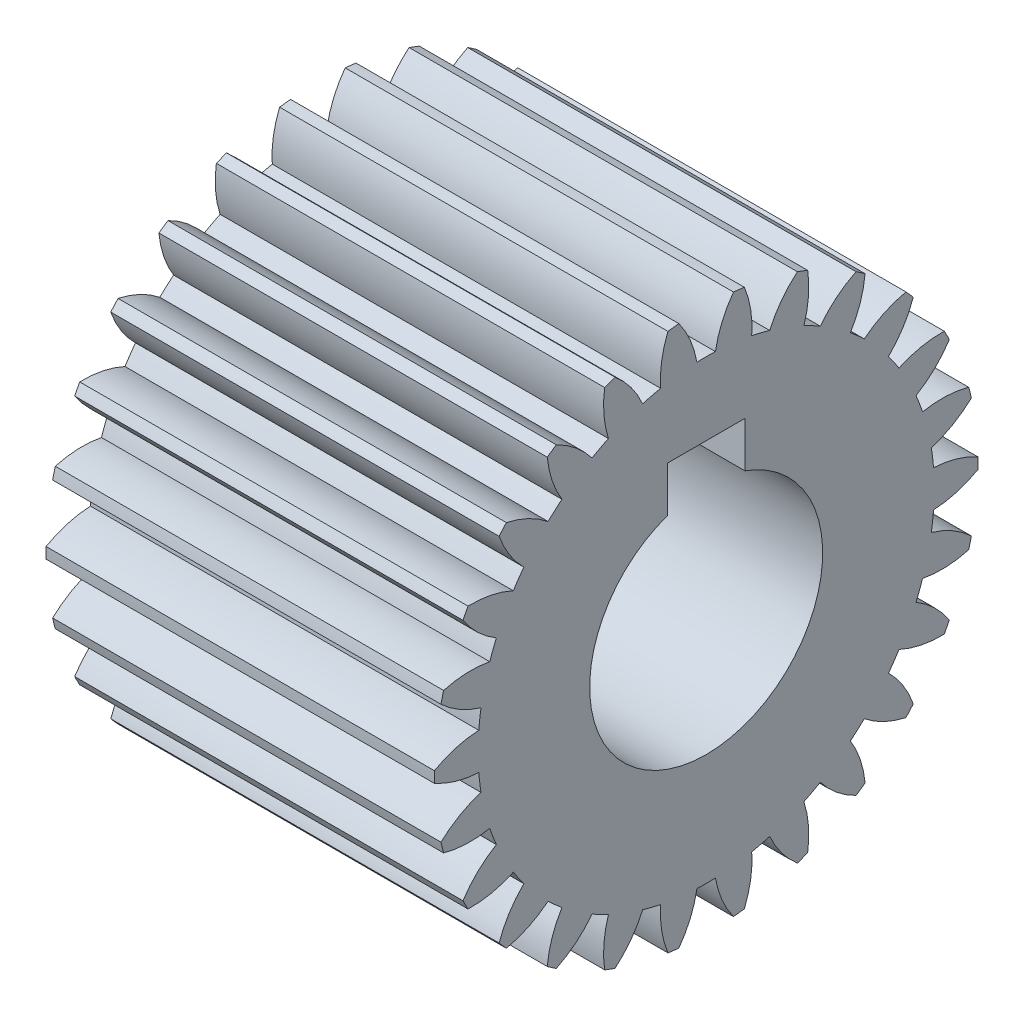
SolidWorks part; units mm, degrees
ref_plane "Plane1" through (0, 0, 0) normal (0, 0, 1) x (1, 0, 0)
ref_plane "Plane2" through (0, 0, 0) normal (0, 1, 0) x (1, 0, 0)
ref_plane "Plane3" through (0, 0, 0) normal (1, 0, 0) x (0, 0, -1)
sketch "HoldingSke" plane through (0, 0, 0) normal (0, 1, 0) x (1, 0, 0)
  line L0 (0, 0) -> (1.7976, -0.8767)
  line L1 (-15, 0) -> (100, 0) construction
  line L2 (0, 0) -> (-2.1039, 2.3779)
  line L3 (0, 0) -> (-11.863, 4.5341)
  line L4 (0, 0) -> (7.762, 3.7858)
  line L5 (0, 0) -> (-46.8476, -17.4728)
  line L6 (0, 0) -> (-8.2896, -5.593)
  line L7 (-2.1039, 2.3779) -> (8.6586, 51.2059)
  line L8 (-76.2, 54.61) -> (-75.2, 54.61)
  line L9 (-71.009, 38.7566) -> (-53.1078, 45.2721)
  line L10 (-76.2, 71.12) -> (104.1128, 71.12)
  line L11 (0, 0) -> (-10, 0)
  line L12 (-76.2, 101.6) -> (-76.181, 101.6)
  line L13 (24.9733, 27.94) -> (52.9518, 28.4284)
  line L14 (24.9733, 27.94) -> (24.9743, 27.94)
  line L15 (24.9733, 27.94) -> (100.4006, 29.5858)
  line L16 (-63.627, -0.5) -> (-12.827, -0.5)
  circle A0 centre (0, 0) radius 3
  circle A1 centre (0, 0) radius 5.874
  circle A2 centre (0, 0) radius 37.5
  circle A3 centre (0, 0) radius 3
  dimension "MHD" = 11.748
  dimension "Hub_dia" = 75
  dimension "Bore" = 6
  dimension "MBD" = 6
  dimension "Num_teeth" = 26
  dimension "Pitch" = 2
  dimension "Overall_len" = 50
  dimension "Show_teeth" = 26
  dimension "Thickness" = 10
  dimension "OAL" = 50.0001
  dimension "T_dim" = 1
  dimension "Ap" = 20
  dimension "H" = 19.05
  dimension "Pitch_radius" = 180.3128
  dimension "Width" = 10
  dimension "Backlash" = 0.019
  dimension "Addendum_fac" = 1
  dimension "Dedendum_fac" = 1.25
  dimension "Clearance_fac" = 0.25
  dimension "Dedendum_add" = 0.001
  dimension "Module" = 0.5
sketch "BasProSke" plane through (0, 0, 0) normal (0, 1, 0) x (1, 0, 0)
  line L0 (-10, 0) -> (60, 0) construction
  line L1 (0, 0) -> (0, 7)
  line L2 (0, 0) -> (10, 0)
  line L3 (10, 0) -> (10, 7)
  line L4 (10, 7) -> (0, 7)
  dimension "Thickness" = 10
  dimension "Diameter" = 14
revolve "Base-Revolve" add sketch "BasProSke" angle 360 about L0
sketch "TooCutSke" plane through (0, 0, 0) normal (1, 0, 0) x (0, 0, -1)
  line L1 (0, 0) -> (0, 107) construction
  line L2 (0, 0) -> (-0.4257, 6.486) construction
  line L3 (0, 0) -> (-1.5646, 12.8855) construction
  line L4 (-0.4257, 6.486) -> (-0.7823, 6.4427) construction
  arc A0 (0.2384, 5.8692) -> (-0.2384, 5.8692) centre (0, 0) ccw
  arc A1 (0.7209, 6.9883) -> (-0.7209, 6.9883) centre (0, 0) ccw
  circle A2 centre (0, 0) radius 6.5 construction
  circle A3 centre (0, 0) radius 6.108 construction
  arc A4 (-0.2384, 5.8692) -> (-0.7209, 6.9883) centre (-2.8007, 5.4281) ccw
  arc A5 (0.7209, 6.9883) -> (0.2384, 5.8692) centre (2.8007, 5.4281) ccw
  dimension "Root_dia" = 11.748
  dimension "Overcut_dia" = 14.0508
  dimension "Pitch_dia" = 13
  dimension "Base_dia" = 12.216
  dimension "Flank_rad" = 2.6
  dimension "Half_ang" = 6.923
  dimension "Half_CT" = 0.3592
extrude "ToothCut" cut sketch "TooCutSke" along normal through all
fillet "Breaks" [suppressed] radius 0.01
fillet "RootFillets" [suppressed] radius 0.126
pattern_circular "TeethCuts" count 26 every 13.846 about axis through (-10, 0, 0) along (1, 0, 0) of "ToothCut", "RootFillets", "Breaks"
sketch "HubNeaOneSke" plane through (0, 0, 0) normal (-1, 0, 0) x (0, 0, 1)
  circle A0 centre (0, 0) radius 5.874
  dimension "Diameter" = 11.748
extrude "HubNearOne" [suppressed] add sketch "HubNeaOneSke" along normal blind 40.0001
sketch "HubNeaBotSke" plane through (0, 0, 0) normal (-1, 0, 0) x (0, 0, 1)
  circle A0 centre (0, 0) radius 5.874
  dimension "Diameter" = 11.748
extrude "HubNearBoth" [suppressed] add sketch "HubNeaBotSke" along normal blind 20
ref_plane "FarPln" through (10, 0, 0) normal (1, 0, 0) x (0, 0, -1)
sketch "HubFarSke" plane through (10, 0, 0) normal (1, 0, 0) x (0, 0, -1)
  circle A0 centre (0, 0) radius 5.874
  dimension "Diameter" = 11.748
extrude "HubFar" [suppressed] add sketch "HubFarSke" along normal blind 20
sketch "BorSke" plane through (0, 0, 0) normal (1, 0, 0) x (0, 0, -1)
  circle A0 centre (0, 0) radius 3
  dimension "Diameter" = 6
extrude "Bore" cut sketch "BorSke" along normal mid plane 100.0001
sketch "KeySke" plane through (0, 0, 0) normal (1, 0, 0) x (0, 0, -1)
  line L0 (-1, 0) -> (-1, 4)
  line L1 (-1, 4) -> (1, 4)
  line L2 (1, 4) -> (1, 0)
  line L3 (0, 0) -> (0, 34) construction
  line L4 (-1, 0) -> (1, 0)
  dimension "Offset" = 4
  dimension "Width" = 2
extrude "Keyway" cut sketch "KeySke" along normal mid plane 100.0001
pattern_circular "Keyway2" [suppressed] count 2 every 90 about axis through (-10, 0, 0) along (1, 0, 0)
equation "' \"Module@HoldingSke\" = 6.35"
equation "' \"Num_teeth@HoldingSke\" = 12"
equation "' \"Ap@HoldingSke\" =  20"
equation "' \"Ap@HoldingSke\" = 20"
equation "' \"Width@HoldingSke\" = 0.5 * 25.4"
equation "' \"Hub_dia@HoldingSke\"= 1 * 25.4"
equation "' \"Hub_dia@HoldingSke\" = 1 * 25.4"
equation "' \"Overall_len@HoldingSke\" = 1.0 * 25.4"
equation "' \"Bore@HoldingSke\" = 0.75 * 25.4"
equation "' \"T_dim@HoldingSke\" = 0.1 * 25.4"
equation "' \"Width@KeySke\" = 0.25 * 25.4"
equation "' \"Show_teeth@HoldingSke\" = 13"
equation "' \"Backlash@HoldingSke\" = 0.009 * 25.4"
equation "' \"Addendum_fac@HoldingSke\" = 1.0"
equation "' \"Dedendum_fac@HoldingSke\" = 1.25"
equation "' \"Dedendum_add@HoldingSke\" = 0.00005 * 25.4"
equation "' \"Clearance_fac@HoldingSke\" = 0.25"
equation "\"Pitch@HoldingSke\" = 1 / \"Module@HoldingSke\""
equation "\"Overcut_dia@TooCutSke\" = (\"Num_teeth@HoldingSke\" + 2 * \"Addendum_fac@HoldingSke\") / \"Pitch@HoldingSke\" + 0.002 * 25.4"
equation "\"Pitch_dia@TooCutSke\" = \"Num_teeth@HoldingSke\" / \"Pitch@HoldingSke\""
equation "\"Base_dia@TooCutSke\" = \"Num_teeth@HoldingSke\" / \"Pitch@HoldingSke\" * cos((\"Ap@HoldingSke\"  * 3.14159265 / 180))"
equation "\"Root_dia@TooCutSke\" = (\"Num_teeth@HoldingSke\" + 2) / \"Pitch@HoldingSke\" - 2 * (\"Addendum_fac@HoldingSke\" + \"Dedendum_fac@HoldingSke\") / \"Pitch@HoldingSke\" - \"Dedendum_add@HoldingSke\" * 2"
equation "\"Half_ang@TooCutSke\" = 180 / \"Num_teeth@HoldingSke\""
equation "\"Half_CT@TooCutSke\" = \"Num_teeth@HoldingSke\" / \"Pitch@HoldingSke\" * sin((3.14159265 / 2 / \"Num_teeth@HoldingSke\")) / 2 - 7 * \"Backlash@HoldingSke\" / 4"
equation "\"Flank_rad@TooCutSke\" = \"Num_teeth@HoldingSke\" / \"Pitch@HoldingSke\" / 5"
equation "\"Radius@RootFillets\" = \"Clearance_fac@HoldingSke\" / \"Pitch@HoldingSke\" + \"Dedendum_add@HoldingSke\""
equation "\"Break_rad@Breaks\" = 0.02 / \"Pitch@HoldingSke\""
equation "\"Thickness@HoldingSke\" = \"Width@HoldingSke\""
equation "\"OAL@HoldingSke\" = \"Thickness@HoldingSke\""
equation "\"MHD@HoldingSke\" = (\"Num_teeth@HoldingSke\" + 2) / \"Pitch@HoldingSke\" - 2 * (\"Addendum_fac@HoldingSke\" + \"Dedendum_fac@HoldingSke\")  / \"Pitch@HoldingSke\" - \"Dedendum_add@HoldingSke\" * 2"
equation "\"MBD@HoldingSke\" = (\"Num_teeth@HoldingSke\" + 2) / \"Pitch@HoldingSke\" - 2 * (\"Addendum_fac@HoldingSke\" + \"Dedendum_fac@HoldingSke\")  / \"Pitch@HoldingSke\" - \"Dedendum_add@HoldingSke\" * 2 - 0.002 * 25.4"
equation "\"MHD@HoldingSke\" = ((sgn( \"MHD@HoldingSke\" - \"Hub_dia@HoldingSke\" )-1)*( \"MHD@HoldingSke\" - \"Hub_dia@HoldingSke\" ))/-2+ \"Hub_dia@HoldingSke\""
equation "\"MBD@HoldingSke\" = ((sgn( \"MBD@HoldingSke\" - \"Bore@HoldingSke\" )-1)*( \"MBD@HoldingSke\" - \"Bore@HoldingSke\" ))/-2+ \"Bore@HoldingSke\""
equation "\"OAL@HoldingSke\" = ((sgn( \"OAL@HoldingSke\" - \"Overall_len@HoldingSke\" )+1)*( \"OAL@HoldingSke\" - \"Overall_len@HoldingSke\" ))/2 + \"Overall_len@HoldingSke\" + 0.000002 * 25.4"
equation "\"Num_teeth@TeethCuts\" = int( \"Show_teeth@HoldingSke\" ) + 1"
equation "\"Num_teeth@TeethCuts\" = ((sgn( \"Num_teeth@TeethCuts\" - \"Num_teeth@HoldingSke\" )-1)*( \"Num_teeth@TeethCuts\" - \"Num_teeth@HoldingSke\" ))/-2+ \"Num_teeth@HoldingSke\""
equation "\"Num_teeth@TeethCuts\" = ((sgn( \"Num_teeth@TeethCuts\" - 2.0)+1)*( \"Num_teeth@TeethCuts\" - 2.0))/2 +2.0"
equation "\"Angle@TeethCuts\" = 360.0 / \"Num_teeth@HoldingSke\""
equation "\"Diameter@BasProSke\" = (\"Num_teeth@HoldingSke\" + 2 * \"Addendum_fac@HoldingSke\") / \"Pitch@HoldingSke\""
equation "\"Thickness@BasProSke\"  = \"Thickness@HoldingSke\""
equation "' \"Fillet_rad@BasProSke\" =  \"Thickness@HoldingSke\" * 0.05"
equation "' \"Fillet_rad@BasProSke\" = \"Thickness@HoldingSke\" * 0.05"
equation "\"MHD@HoldingSke\" = ((sgn( \"MHD@HoldingSke\" - \"Root_dia@TooCutSke\" )-1)*( \"MHD@HoldingSke\" - \"Root_dia@TooCutSke\" ))/-2+ \"Root_dia@TooCutSke\""
equation "\"Diameter@HubNeaOneSke\" = \"MHD@HoldingSke\""
equation "\"Length@HubNearOne\" = \"OAL@HoldingSke\" - \"Thickness@BasProSke\""
equation "\"Diameter@HubNeaBotSke\" = \"MHD@HoldingSke\""
equation "\"Length@HubNearBoth\" = ( \"OAL@HoldingSke\" - \"Thickness@BasProSke\" ) / 2.0"
equation "\"Thickness@FarPln\" = \"Thickness@BasProSke\""
equation "\"Diameter@HubFarSke\" = \"MHD@HoldingSke\""
equation "\"Length@HubFar\" = ( \"OAL@HoldingSke\" - \"Thickness@BasProSke\" ) / 2.0"
equation "\"Diameter@BorSke\" = \"MBD@HoldingSke\""
equation "\"D1@Bore\" = \"OAL@HoldingSke\" * 2.0"
equation "\"D1@Keyway\" = \"OAL@HoldingSke\" * 2.0"
equation "\"Offset@KeySke\" = \"T_dim@HoldingSke\" + \"MBD@HoldingSke\" / 2.0"
